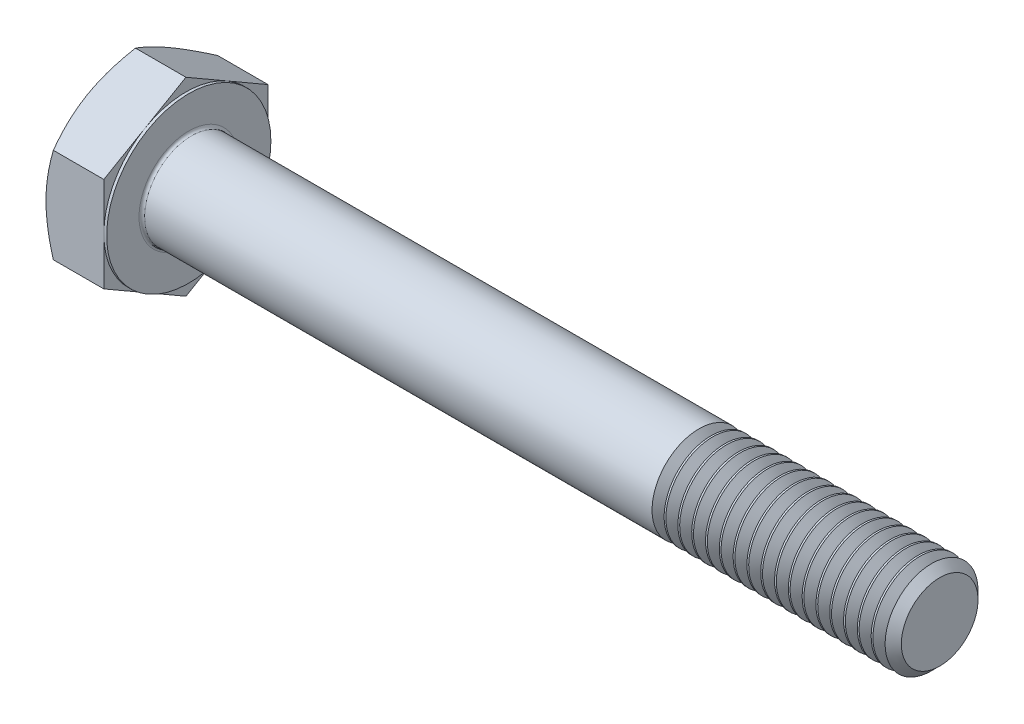
SolidWorks part; units mm, degrees
extrude "BaseHead" add sketch "Sketch1" along normal blind 8.2042
sketch "Sketch1" plane through (0, 0, 0) normal (1, 0, 0) x (0, 0, -1)
  line L0 (11.1125, 6.4158) -> (11.1125, -6.4158)
  line L1 (-11.1125, 6.4158) -> (-11.1125, -6.4158)
  line L2 (11.1125, -6.4158) -> (0, -12.8316)
  line L3 (0, -12.8316) -> (-11.1125, -6.4158)
  line L4 (11.1125, 6.4158) -> (0, 12.8316)
  line L5 (0, 12.8316) -> (-11.1125, 6.4158)
  dimension "Width_flats" = 22.225
  dimension "D2" = 120
  dimension "D3" = 11.1125
  dimension "D4" = 11.1125
  dimension "D5" = 11.1125
revolve "HeadChamfer" cut sketch "Sketch3" angle 360 about L6
sketch "Sketch3" plane through (0, 0, 0) normal (0, 0, 1) x (1, 0, 0)
  line L0 (0, 11.1125) -> (4.6587, 19.1816)
  line L1 (0, 12.8316) -> (0, 6.4158) construction
  line L2 (4.6587, 19.1816) -> (4.6587, 25.5316)
  line L3 (4.6587, 25.5316) -> (-12.7, 25.5316)
  line L4 (-12.7, 25.5316) -> (-12.7, 11.1125)
  line L5 (-12.7, 11.1125) -> (0, 11.1125)
  line L6 (0, 0) -> (99.06, 0) construction
  line L7 (8.2042, 12.8316) -> (0, 12.8316) construction
  dimension "D1" = 11.1125
  dimension "D2" = 6.35
  dimension "D3" = 12.7
  dimension "D4" = 6.35
  dimension "Head_ch_ang" = 30
ref_plane "Plane1" through (0, 0, 0) normal (0, 0, 1) x (1, 0, 0)
ref_plane "Plane2" through (0, 0, 0) normal (0, 1, 0) x (1, 0, 0)
ref_plane "Plane3" through (0, 0, 0) normal (1, 0, 0) x (0, 0, -1)
sketch "BodySke" plane through (0, 0, 0) normal (0, 0, 1) x (1, 0, 0)
  line L0 (0, 6.4158) -> (0, -6.4158) construction
  line L1 (0, 0) -> (109.8042, 0)
  line L2 (0, 0) -> (0, 6.35)
  line L3 (0, 6.35) -> (108.6409, 6.35)
  line L4 (109.8042, 0) -> (109.8042, 5.1867)
  line L5 (8.2042, 12.8316) -> (8.2042, 6.4158) construction
  line L6 (109.8042, 5.1867) -> (108.6409, 6.35)
  line L7 (0, 0) -> (96.52, 0) construction
  line L8 (109.8042, -5.1867) -> (108.6409, -6.35) construction
  line L9 (0, -6.35) -> (108.6409, -6.35) construction
  line L10 (10.1575, 15.24) -> (10.1575, -1.27) construction
  line L11 (78.0542, 15.24) -> (78.0542, -1.27) construction
  line L12 (8.2042, 6.4158) -> (8.2042, -6.4158) construction
  dimension "Diameter" = 12.7
revolve "BaseBody" add sketch "BodySke" angle 360 about L7
cosmetic thread "ThreadCosmetic" [suppressed] parameters "Thread_length"=31.75, "Thread_minor"=10.3734
sketch "Sketch4" plane through (0, 0, 0) normal (0, 0, 1) x (1, 0, 0)
  line L1 (8.2042, 12.8316) -> (8.2042, 6.4158) construction
  line L2 (8.2042, 11.1125) -> (7.8232, 11.1125)
  line L3 (8.2042, 11.1125) -> (8.2042, 38.2316)
  line L4 (8.2042, 38.2316) -> (7.8232, 38.2316)
  line L5 (0, 0) -> (95.25, 0) construction
  line L6 (0, 0) -> (96.52, 0) construction
  line L7 (7.8232, 11.1125) -> (7.8232, 38.2316)
  line L8 (8.2042, 12.8316) -> (0.9925, 12.8316) construction
  dimension "D1" = 11.1125
  dimension "D2" = 25.4
revolve "BearingFace" cut sketch "Sketch4" angle 360 about L5
fillet "HeadFillet" radius 0.381 1 edges at (8.2042, 0, -6.35)
sketch "ThdSchSke" plane through (0, 0, 0) normal (0, 0, 1) x (1, 0, 0)
  line L0 (78.0542, -5.1867) -> (77.2396, -6.35)
  line L1 (78.0542, -5.1867) -> (78.8688, -6.35)
  line L2 (78.8688, -6.35) -> (78.8688, -7.9375)
  line L3 (-3.175, 0) -> (5.1513, 0) construction
  line L5 (78.8688, -7.9375) -> (77.2396, -7.9375)
  line L6 (77.2396, -7.9375) -> (77.2396, -6.35)
  dimension "Thread_minor" = 10.3734
  dimension "Diameter" = 12.7
  dimension "Start" = 78.0542
revolve "ThreadSchematic" cut sketch "ThdSchSke" angle 360 about L3
pattern_linear "ThdSchPat" count 17 spacing 1.8676 along (1, 0, 0) of "ThreadSchematic"
equation "\"D3@Sketch1\" = \"Width_flats@Sketch1\" / 2"
equation "\"D4@Sketch1\" = \"D3@Sketch1\""
equation "\"D5@Sketch1\" = \"D4@Sketch1\""
equation "\"Thread_minor@ThreadCosmetic\" = \"Minor_dia@BodySke\""
equation "\"D1@Sketch3\" = \"Width_flats@Sketch1\" / 2"
equation "\"D1@Sketch4\" = \"Width_flats@Sketch1\" / 2"
equation "\"Thread_length@ThreadCosmetic\" = ((sgn( (\"Length@BodySke\" - \"Advance@BodySke\" ) - \"Thread_nom@BodySke\" )-1)*( (\"Length@BodySke\" - \"Advance@BodySke\" ) - \"Thread_nom@BodySke\" ))/-2+ \"Thread_nom@BodySke\""
equation "\"Thread_minor@ThdSchSke\" = \"Minor_dia@BodySke\""
equation "\"Diameter@ThdSchSke\" = \"Diameter@BodySke\""
equation "\"Overcut@ThdSchSke\" = \"Diameter@BodySke\" * 1.25"
equation "\"Start@ThdSchSke\" = \"Head_ht@BaseHead\" + \"Length@BodySke\" - \"Thread_length@ThreadCosmetic\"  '---Non-countersunk---"
equation "\"Num_threads@ThdSchPat\" = int( \"Thread_length@ThreadCosmetic\" / \"Advance@BodySke\" + 0.999 )  + 1"
equation "\"Advance@ThdSchPat\" = \"Thread_length@ThreadCosmetic\" /  (\"Num_threads@ThdSchPat\" - 1) 'relax it"
equation "\"Num_threads@ThdSchPat\" = \"Num_threads@ThdSchPat\" - sgn( \"Num_threads@ThdSchPat\" - 1) '---chamfered tips only---"
